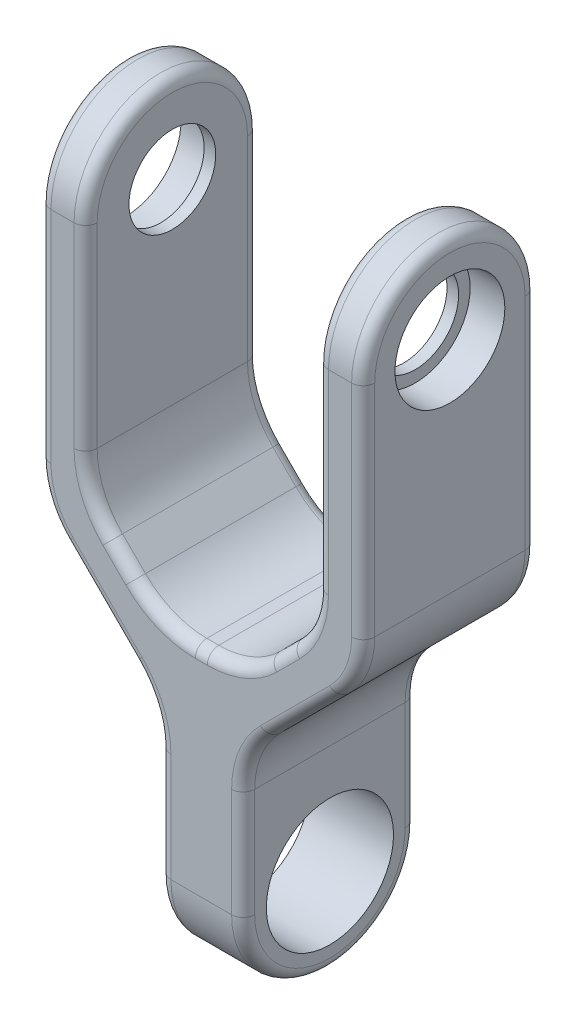
SolidWorks part; units mm, degrees
ref_plane "前视基准面" through (0, 0, 0) normal (0, 0, 1) x (1, 0, 0)
ref_plane "上视基准面" through (0, 0, 0) normal (0, 1, 0) x (1, 0, 0)
ref_plane "右视基准面" through (0, 0, 0) normal (1, 0, 0) x (0, 0, -1)
sketch "草图1" plane through (0, 0, 0) normal (0, 0, 1) x (1, 0, 0)
  line L0 (0, 0) -> (14.5, 0)
  line L1 (14.5, 0) -> (14.5, 25)
  line L2 (14.5, 25) -> (35.25, 45.75)
  line L3 (35.25, 45.75) -> (35.25, 90)
  line L4 (35.25, 90) -> (27.25, 90)
  line L5 (27.25, 90) -> (27.25, 50)
  line L6 (27.25, 50) -> (-12.75, 50)
  line L7 (-12.75, 50) -> (-12.75, 90)
  line L8 (-12.75, 90) -> (-20.75, 90)
  line L9 (-20.75, 90) -> (-20.75, 45.75)
  line L11 (0, 25) -> (0, 0)
  line L12 (0, 25) -> (-20.75, 45.75)
  line L13 (7.25, 0) -> (7.25, 35.1674) construction
  dimension "D1" = 135
  dimension "D2" = 135
  dimension "D3" = 14.5
  dimension "D4" = 8
  dimension "D5" = 8
  dimension "D6" = 40
  dimension "D7" = 90
  dimension "D8" = 25
  dimension "D9" = 40
extrude "凸台-拉伸1" add sketch "草图1" along normal blind 30
sketch "草图2" plane through (0, 0, 30) normal (0, 0, 1) x (1, 0, 0)
  line L0 (-12.75, 50) -> (0, 37.25)
  line L1 (0, 37.25) -> (14.5, 37.25)
  line L2 (14.5, 37.25) -> (27.25, 50)
  line L3 (-20.75, 45.75) -> (0, 25) construction
  line L4 (14.5, 25) -> (35.25, 45.75) construction
  line L5 (-12.75, 50) -> (27.25, 50)
extrude "切除-拉伸1" cut sketch "草图2" against normal through all
sketch "草图3" plane through (14.5, 0, 0) normal (1, 0, 0) x (0, 0, -1)
  line L0 (-30, 0) -> (0, 0)
  arc A0 (-30, 0) -> (0, 0) centre (-15, 0) ccw
extrude "凸台-拉伸2" add sketch "草图3" against normal up to surface (14.5 mm away) up to face at (0, 12.5, 15)
sketch "草图4" plane through (14.5, 0, 0) normal (1, 0, 0) x (0, 0, -1)
  circle A0 centre (-15, 0) radius 11
  dimension "D1" = 22
extrude "切除-拉伸2" cut sketch "草图4" against normal blind 20
sketch "草图5" plane through (14.5, 0, 0) normal (1, 0, 0) x (0, 0, -1)
  circle A0 centre (-15, 0) radius 9.5
  dimension "D1" = 19
extrude "切除-拉伸3" [suppressed] cut sketch "草图5" against normal blind 6
sketch "草图6" plane through (0, 0, 0) normal (-1, 0, 0) x (0, 0, 1)
  circle A0 centre (15, 0) radius 9.5
  dimension "D1" = 19
extrude "切除-拉伸4" [suppressed] cut sketch "草图6" against normal blind 6
sketch "草图7" plane through (35.25, 0, 0) normal (1, 0, 0) x (0, 0, -1)
  line L0 (-30, 90) -> (0, 90)
  arc A0 (-30, 90) -> (0, 90) centre (-15, 90) cw
extrude "凸台-拉伸3" add sketch "草图7" against normal up to surface (8 mm away) up to face at (27.25, 70, 15)
sketch "草图8" plane through (-20.75, 0, 0) normal (-1, 0, 0) x (0, 0, 1)
  line L0 (0, 90) -> (30, 90)
  arc A0 (0, 90) -> (30, 90) centre (15, 90) cw
extrude "凸台-拉伸4" add sketch "草图8" against normal up to surface (8 mm away) up to face at (-12.75, 70, 15)
sketch "草图9" plane through (-20.75, 0, 0) normal (-1, 0, 0) x (0, 0, 1)
  circle A0 centre (15, 90) radius 7.5
  dimension "D1" = 15
extrude "切除-拉伸5" cut sketch "草图9" against normal blind 62
sketch "草图10" plane through (-20.75, 0, 0) normal (-1, 0, 0) x (0, 0, 1)
  circle A0 centre (15, 90) radius 9.5
  dimension "D1" = 19
extrude "切除-拉伸6" cut sketch "草图10" against normal blind 6
sketch "草图11" plane through (35.25, 0, 0) normal (1, 0, 0) x (0, 0, -1)
  circle A0 centre (-15, 90) radius 9.5
  dimension "D1" = 19
extrude "切除-拉伸7" cut sketch "草图11" against normal blind 6
fillet "圆角1" radius 15 8 edges at (-12.75, 50, 15) (0, 37.25, 15) (14.5, 37.25, 15) (27.25, 50, 15) (0, 25, 15) (-20.75, 45.75, 15) (14.5, 25, 15) (35.25, 45.75, 15)
fillet "圆角2" radius 2 44 edges at (7.25, 37.25, 30) (14.027, 38.3918, 30) (20.875, 43.625, 30) (26.1082, 50.473, 30) (27.25, 73.1066, 30) (27.25, 105, 15) (35.25, 105, 15) (27.25, 73.1066, 0) (26.1082, 50.473, 0) (20.875, 43.625, 0) (14.027, 38.3918, 0) (7.25, 37.25, 0) (0.473, 38.3918, 0) (-6.375, 43.625, 0) (-11.6082, 50.473, 0) (-12.75, 73.1066, 0) (-12.75, 105, 15) (-20.75, 105, 15) (-12.75, 73.1066, 30) (-11.6082, 50.473, 30) (-6.375, 43.625, 30) (14.5, 9.3934, 30) (0, -15, 15) (14.5, -15, 15) (14.5, 9.3934, 0) (15.6418, 24.527, 0) (24.875, 35.375, 0) (34.1082, 46.223, 0) (35.25, 70.9816, 0) (35.25, 70.9816, 30) (34.1082, 46.223, 30) (24.875, 35.375, 30) (-19.6082, 46.223, 30) (-20.75, 70.9816, 30) (-20.75, 70.9816, 0) (-19.6082, 46.223, 0) (-10.375, 35.375, 0) (-1.1418, 24.527, 0) (0, 9.3934, 0) (0, 9.3934, 30) (-1.1418, 24.527, 30) (0.473, 38.3918, 30) (15.6418, 24.527, 30) (-10.375, 35.375, 30)
